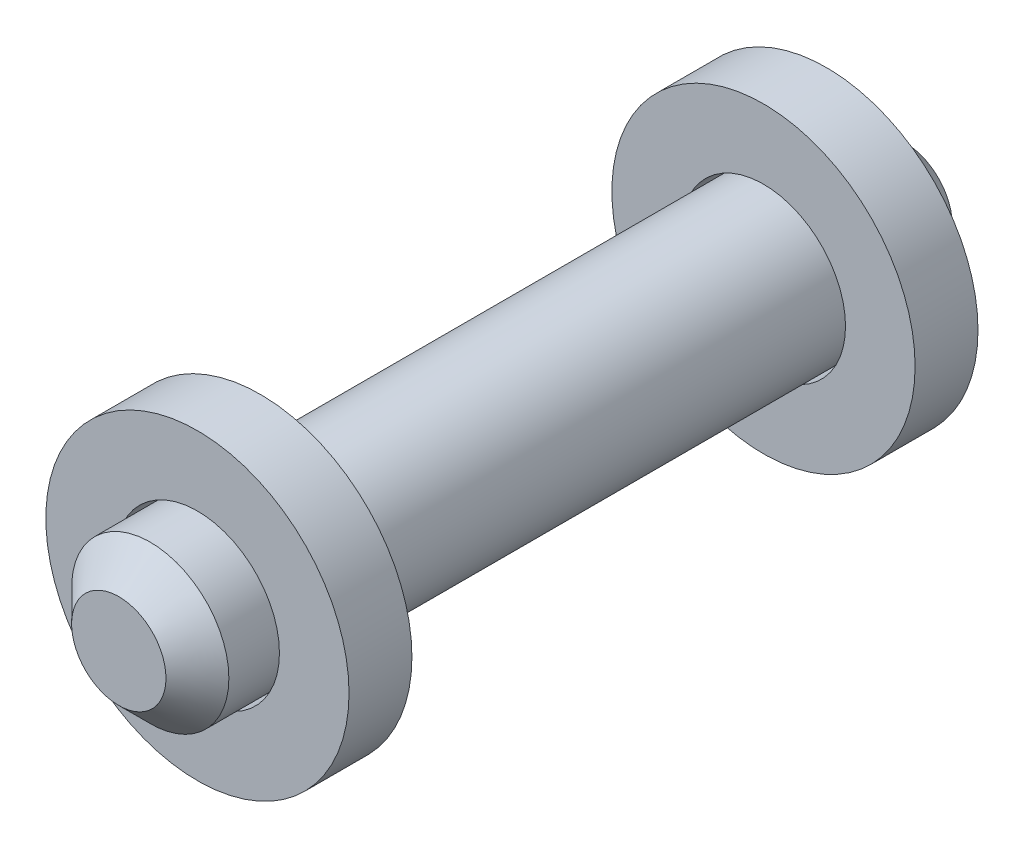
SolidWorks part; units mm, degrees
ref_plane "Front Plane" through (0, 0, 0) normal (0, 0, 1) x (1, 0, 0)
ref_plane "Top Plane" through (0, 0, 0) normal (0, 1, 0) x (1, 0, 0)
ref_plane "Right Plane" through (0, 0, 0) normal (1, 0, 0) x (0, 0, -1)
sketch "Sketch1" plane through (0, 0, 0) normal (0, 0, 1) x (1, 0, 0)
  circle A0 centre (0, 0) radius 2.5
  dimension "D1" = 5
extrude "Boss-Extrude1" add sketch "Sketch1" along normal mid plane 25
chamfer "Chamfer1" distance 1 angle 45 2 edges at (2.5, 0, -12.5) (2.5, 0, 12.5)
ref_plane "Plane1" through (0, 0, 8) normal (0, 0, 1) x (1, 0, 0)
sketch "Sketch2" plane through (0, 0, 8) normal (0, 0, 1) x (1, 0, 0)
  circle A0 centre (0, 0) radius 2.6077
  circle A1 centre (0, 0) radius 4.8208
extrude "Boss-Extrude2" add sketch "Sketch2" along normal blind 2 separate body
mirror "Mirror2" about plane through (0, 0, 0) normal (0, 0, 1) of bodies 102
